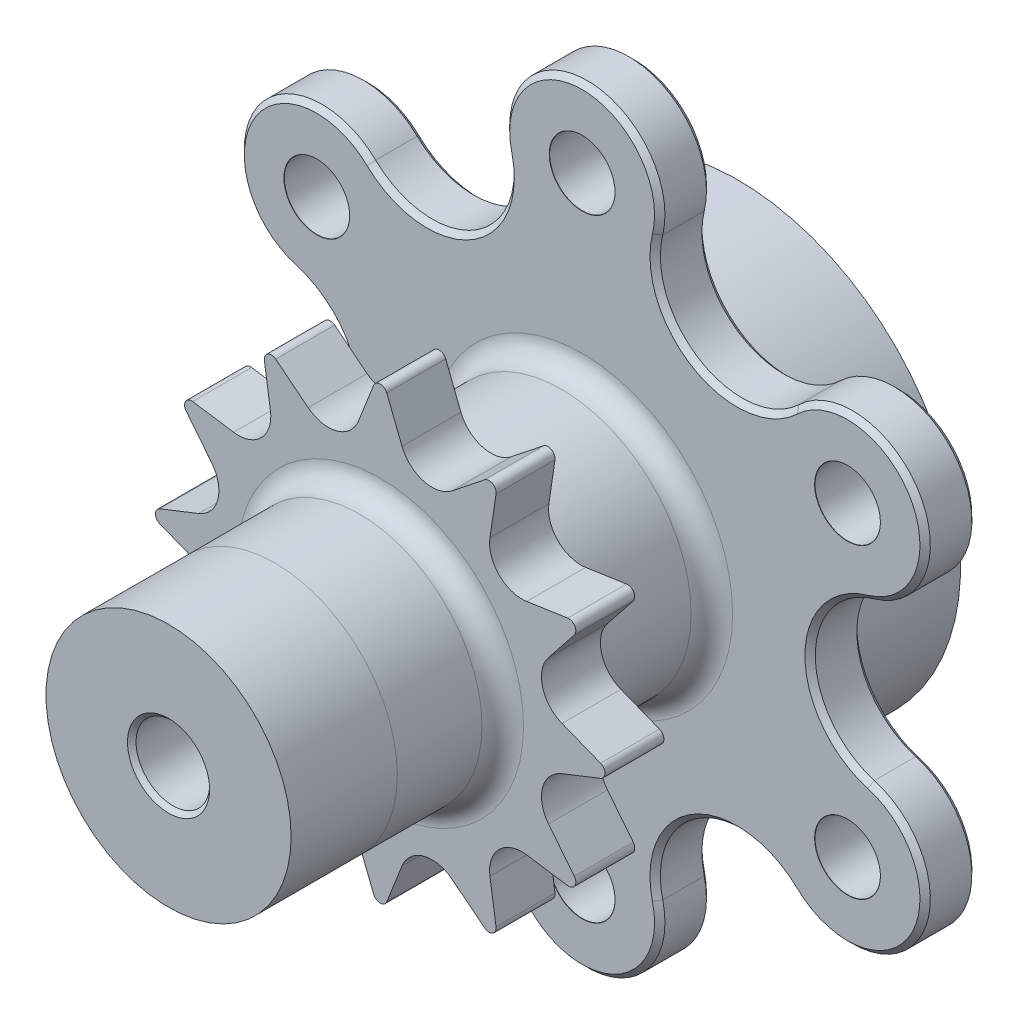
SolidWorks part; units mm, degrees
material "AISI 4130 Steel, normalized at 870C"
ref_plane "Front Plane" through (0, 0, 0) normal (0, 0, 1) x (1, 0, 0)
ref_plane "Top Plane" through (0, 0, 0) normal (0, 1, 0) x (1, 0, 0)
ref_plane "Right Plane" through (0, 0, 0) normal (1, 0, 0) x (0, 0, -1)
sketch "Sketch1" plane through (0, 0, 0) normal (0, 0, 1) x (1, 0, 0)
  circle A0 centre (0, 0) radius 47
  dimension "D1" = 94
extrude "Boss-Extrude1" add sketch "Sketch1" along normal blind 6.35
hole_wizard "Ø8.0mm Dowel Hole1" positions "Sketch3" profile "Sketch4" hole size "Ø8.0" standard "ANSI Metric" end condition through all
sketch "Sketch3" plane through (0, 0, 6.35) normal (0, 0, 1) x (1, 0, 0)
  point P0 (0, -37.5)
  dimension "D1" = 37.5
sketch "Sketch4" plane through (0, -37.5, 6.35) normal (1, 0, 0) x (0, -1, 0)
  line L0 (0, 0) -> (0, 6.35)
  line L1 (0, 6.35) -> (4, 6.35)
  line L2 (4, 6.35) -> (4, 0.025)
  line L3 (4, 0.025) -> (4.025, 0)
  line L5 (4.025, 0) -> (0, 0)
  line L6 (-4, 0.025) -> (-4.025, 0) construction
  line L11 (0, -6.35) -> (0, 107.95) construction
  dimension "Thru Hole Dia." = 8
  dimension "Thru Hole Depth" = 6.35
  dimension "Near C'Sink Dia." = 8.05
  dimension "Near C'Sink Angle" = 90
pattern_circular "CirPattern1" count 6 over 360 about axis through (0, 0, 0) along (0, 0, 1) of "Ø8.0mm Dowel Hole1"
sketch "Sketch5" plane through (0, 0, 6.35) normal (0, 0, 1) x (1, 0, 0)
  circle A0 centre (0, -37.5) radius 9.5 construction
  circle A1 centre (0, 0) radius 47 construction
  circle A2 centre (0, 0) radius 47
  circle A3 centre (-32.476, -18.75) radius 9.5 construction
  circle A4 centre (-32.476, 18.75) radius 9.5 construction
  circle A5 centre (0, 37.5) radius 9.5 construction
  circle A6 centre (32.476, 18.75) radius 9.5 construction
  circle A7 centre (32.476, -18.75) radius 9.5 construction
  circle A8 centre (0, 0) radius 27.9 construction
  arc A9 (-25.9015, 25.6076) -> (-9.2261, 35.2352) centre (-18.963, 32.8449) ccw
  arc A10 (9.2261, 35.2352) -> (25.9015, 25.6076) centre (18.963, 32.8449) ccw
  arc A11 (35.1276, 9.6276) -> (35.1276, -9.6276) centre (37.926, 0) ccw
  arc A12 (25.9015, -25.6076) -> (9.2261, -35.2352) centre (18.963, -32.8449) ccw
  arc A13 (-9.2261, -35.2352) -> (-25.9015, -25.6076) centre (-18.963, -32.8449) ccw
  arc A14 (-35.1276, -9.6276) -> (-35.1276, 9.6276) centre (-37.926, 0) ccw
  arc A15 (-9.2261, 35.2352) -> (9.2261, 35.2352) centre (0, 37.5) cw
  arc A16 (-25.9015, 25.6076) -> (-35.1276, 9.6276) centre (-32.476, 18.75) ccw
  arc A17 (-35.1276, -9.6276) -> (-25.9015, -25.6076) centre (-32.476, -18.75) ccw
  arc A18 (-9.2261, -35.2352) -> (9.2261, -35.2352) centre (0, -37.5) ccw
  arc A19 (25.9015, -25.6076) -> (35.1276, -9.6276) centre (32.476, -18.75) ccw
  arc A20 (25.9015, 25.6076) -> (35.1276, 9.6276) centre (32.476, 18.75) cw
  point P19 (0, 0)
  point P38 (0, 0)
  circle M13 centre (0, 0) radius 47
  dimension "D1" = 6
  dimension "D2" = 55.8
  dimension "D3" = 6
extrude "Cut-Extrude1" cut sketch "Sketch5" against normal through all contours A16 A9 A15 M13 | A10 A20 A2 A15 | A17 A14 A16 A2 | A18 A13 A17 M13 | A19 A12 A18 A2 | A20 A11 A19 M13
chamfer "Chamfer1" distance 0.635 angle 45 24 edges at (-40.7032, 23.5, 6.35) (-27.9, 0, 6.35) (-40.7032, -23.5, 6.35) (-13.95, -24.1621, 6.35) (0, -47, 6.35) (13.95, -24.1621, 6.35) (40.7032, -23.5, 6.35) (27.9, 0, 6.35) (40.7032, 23.5, 6.35) (13.95, 24.1621, 6.35) (0, 47, 6.35) (-13.95, 24.1621, 6.35) (0, -47, 0) (-13.95, -24.1621, 0) (13.95, -24.1621, 0) (-40.7032, -23.5, 0) (40.7032, -23.5, 0) (-27.9, 0, 0) (27.9, 0, 0) (-40.7032, 23.5, 0) (40.7032, 23.5, 0) (-13.95, 24.1621, 0) (13.95, 24.1621, 0) (0, 47, 0)
sketch "Sketch6" [suppressed] plane through (0, 0, 6.35) normal (0, 0, 1) x (1, 0, 0)
  circle A0 centre (0, 0) radius 15.875
  dimension "D1" = 31.75
extrude "Shaft" [suppressed] add sketch "Sketch6" along normal blind 53.848
sketch "Sketch7" [suppressed] plane through (0, 0, 60.198) normal (0, 0, 1) x (1, 0, 0)
  arc A0 (9.097, -5.6181) -> (9.7313, -4.4292) centre (0, 0) ccw
  arc A1 (9.097, -5.6181) -> (9.0986, -5.9863) centre (9.3955, -5.8008) ccw
  arc A2 (10.055, -4.164) -> (9.7313, -4.4292) centre (10.071, -4.5136) ccw
  arc A3 (12.1705, -3.6562) -> (12.3739, -3.4251) centre (12.0362, -3.333) ccw
  arc A4 (12.3739, -3.4251) -> (12.5248, -2.8127) centre (0.0056, -0.0518) ccw
  arc A5 (9.3895, -8.7865) -> (9.8078, -8.3144) centre (0.0056, -0.0518) ccw
  arc A6 (4.2554, -12.1469) -> (4.8452, -11.9232) centre (0.0056, -0.0518) ccw
  arc A7 (-1.8522, -12.7365) -> (-1.2261, -12.8125) centre (0.0056, -0.0518) ccw
  arc A8 (-7.5343, -10.4201) -> (-7.0152, -10.7784) centre (0.0056, -0.0518) ccw
  arc A9 (-11.489, -5.7285) -> (-11.1959, -6.287) centre (0.0056, -0.0518) ccw
  arc A10 (-12.8144, -0.0518) -> (-12.8105, -0.3671) centre (0.0056, -0.0518) ccw
  arc A11 (12.533, -2.7373) -> (12.4521, -2.5135) centre (12.183, -2.7373) ccw
  arc A12 (12.5248, -2.8127) -> (12.533, -2.7373) centre (12.183, -2.7373) ccw
  arc A13 (10.6424, -0.7555) -> (10.815, -1.0808) centre (10.9916, -0.7786) ccw
  arc A14 (10.6424, -0.7555) -> (10.6656, -0.0518) centre (0.0056, -0.0518) ccw
  arc A15 (10.6656, -0.0518) -> (10.6424, 0.6519) centre (0.0056, -0.0518) ccw
  arc A16 (10.815, 0.9772) -> (10.6424, 0.6519) centre (10.9916, 0.6751) ccw
  arc A17 (12.4521, 2.41) -> (12.533, 2.6337) centre (12.183, 2.6337) ccw
  arc A18 (-12.8105, 0.2636) -> (-12.8144, -0.0518) centre (0.0056, -0.0518) ccw
  arc A19 (-11.1959, 6.1834) -> (-11.489, 5.6249) centre (0.0056, -0.0518) ccw
  arc A20 (-7.0152, 10.6748) -> (-7.5343, 10.3165) centre (0.0056, -0.0518) ccw
  arc A21 (-1.2261, 12.7089) -> (-1.8522, 12.6329) centre (0.0056, -0.0518) ccw
  arc A22 (4.8452, 11.8197) -> (4.2554, 12.0433) centre (0.0056, -0.0518) ccw
  arc A23 (9.8078, 8.2108) -> (9.3895, 8.6829) centre (0.0056, -0.0518) ccw
  arc A24 (12.5248, 2.7091) -> (12.3739, 3.3215) centre (0.0056, -0.0518) ccw
  arc A25 (12.533, 2.6337) -> (12.5248, 2.7091) centre (12.183, 2.6337) ccw
  arc A26 (12.3739, 3.3215) -> (12.1705, 3.5526) centre (12.0362, 3.2294) ccw
  arc A27 (9.751, 4.2682) -> (10.055, 4.0604) centre (10.071, 4.4101) ccw
  arc A28 (9.751, 4.2682) -> (9.097, 5.5145) centre (0.0056, -0.0518) ccw
  arc A29 (9.0986, 5.8827) -> (9.097, 5.5145) centre (9.3955, 5.6972) ccw
  arc A30 (9.8901, 7.9852) -> (9.8078, 8.2108) centre (9.5401, 7.9852) ccw
  arc A31 (9.8824, 7.9122) -> (9.8901, 7.9852) centre (9.5401, 7.9852) ccw
  arc A32 (9.3895, 8.6829) -> (9.102, 8.793) centre (9.1333, 8.4444) ccw
  arc A33 (6.6272, 8.3023) -> (5.4688, 9.1018) centre (0.0056, -0.0518) ccw
  arc A34 (6.6272, 8.3023) -> (6.9929, 8.2596) centre (6.8446, 8.5766) ccw
  arc A35 (5.2992, 9.4287) -> (5.4688, 9.1018) centre (5.6482, 9.4024) ccw
  arc A36 (5.0501, 11.5899) -> (4.8452, 11.8197) centre (4.713, 11.4956) ccw
  arc A37 (4.2554, 12.0433) -> (3.9497, 12.0072) centre (4.1394, 11.7131) ccw
  arc A38 (1.9864, 10.4226) -> (0.5891, 10.5922) centre (0.0056, -0.0518) ccw
  arc A39 (1.9864, 10.4226) -> (2.3301, 10.5547) centre (2.0514, 10.7665) ccw
  arc A40 (0.2871, 10.8028) -> (0.5891, 10.5922) centre (0.6083, 10.9417) ccw
  arc A41 (-0.9379, 12.6007) -> (-1.2261, 12.7089) centre (-1.1925, 12.3605) ccw
  arc A42 (-1.8522, 12.6329) -> (-2.1062, 12.4588) centre (-1.8015, 12.2866) ccw
  arc A43 (-3.1082, 10.1433) -> (-4.4242, 9.6442) centre (0.0056, -0.0518) ccw
  arc A44 (-3.1082, 10.1433) -> (-2.8653, 10.42) centre (-3.2104, 10.478) ccw
  arc A45 (-4.7895, 9.6902) -> (-4.4242, 9.6442) centre (-4.5697, 9.9625) ccw
  arc A46 (-6.7097, 10.7129) -> (-7.0152, 10.6748) centre (-6.8235, 10.382) ccw
  arc A47 (-7.5343, 10.3165) -> (-7.6783, 10.0444) centre (-7.3284, 10.0335) ccw
  arc A48 (-7.4894, 7.5284) -> (-7.3855, 7.7773) centre (-7.7355, 7.7773) ccw
  arc A49 (-7.4894, 7.5284) -> (-8.4227, 6.4749) centre (0.0056, -0.0518) ccw
  arc A50 (-7.3855, 7.7773) -> (-7.4029, 7.8863) centre (-7.7355, 7.7773) ccw
  arc A51 (-8.7676, 6.3459) -> (-8.4227, 6.4749) centre (-8.6995, 6.6892) ccw
  arc A52 (-10.9431, 6.3591) -> (-11.1959, 6.1834) centre (-10.8901, 6.0132) ccw
  arc A53 (-11.489, 5.6249) -> (-11.4901, 5.3171) centre (-11.1752, 5.4699) ccw
  arc A54 (-10.1536, 3.177) -> (-10.4904, 1.8105) centre (0.0056, -0.0518) ccw
  arc A55 (-10.1372, 3.2831) -> (-10.2433, 3.5342) centre (-10.4872, 3.2831) ccw
  arc A56 (-10.1536, 3.177) -> (-10.1372, 3.2831) centre (-10.4872, 3.2831) ccw
  arc A57 (-10.7359, 1.536) -> (-10.4904, 1.8105) centre (-10.8351, 1.8716) ccw
  arc A58 (-12.6683, 0.5366) -> (-12.8105, 0.2636) centre (-12.4606, 0.255) ccw
  arc A59 (-12.8105, -0.3671) -> (-12.6683, -0.6402) centre (-12.4606, -0.3585) ccw
  arc A60 (-10.4904, -1.914) -> (-10.7359, -1.6395) centre (-10.8351, -1.9752) ccw
  arc A61 (-10.4904, -1.914) -> (-10.1536, -3.2806) centre (0.0056, -0.0518) ccw
  arc A62 (-10.1372, -3.3866) -> (-10.1536, -3.2806) centre (-10.4872, -3.3866) ccw
  arc A63 (-10.2433, -3.6377) -> (-10.1372, -3.3866) centre (-10.4872, -3.3866) ccw
  arc A64 (-11.4901, -5.4206) -> (-11.489, -5.7285) centre (-11.1752, -5.5735) ccw
  arc A65 (-11.1959, -6.287) -> (-10.9431, -6.4627) centre (-10.8901, -6.1167) ccw
  arc A66 (-8.4227, -6.5785) -> (-8.7676, -6.4495) centre (-8.6995, -6.7928) ccw
  arc A67 (-8.4227, -6.5785) -> (-7.4894, -7.632) centre (0.0056, -0.0518) ccw
  arc A68 (-7.3855, -7.8809) -> (-7.4894, -7.632) centre (-7.7355, -7.8809) ccw
  arc A69 (-7.4029, -7.9899) -> (-7.3855, -7.8809) centre (-7.7355, -7.8809) ccw
  arc A70 (-7.6783, -10.148) -> (-7.5343, -10.4201) centre (-7.3284, -10.137) ccw
  arc A71 (-7.0152, -10.7784) -> (-6.7097, -10.8165) centre (-6.8235, -10.4855) ccw
  arc A72 (-4.4242, -9.7478) -> (-4.7895, -9.7938) centre (-4.5697, -10.0661) ccw
  arc A73 (-4.4242, -9.7478) -> (-3.1082, -10.2469) centre (0.0056, -0.0518) ccw
  arc A74 (-2.8653, -10.5236) -> (-3.1082, -10.2469) centre (-3.2104, -10.5816) ccw
  arc A75 (-2.1062, -12.5624) -> (-1.8522, -12.7365) centre (-1.8015, -12.3901) ccw
  arc A76 (-1.2261, -12.8125) -> (-0.9379, -12.7043) centre (-1.1925, -12.4641) ccw
  arc A77 (0.5891, -10.6958) -> (1.9864, -10.5262) centre (0.0056, -0.0518) ccw
  arc A78 (0.5891, -10.6958) -> (0.2871, -10.9063) centre (0.6083, -11.0453) ccw
  arc A79 (2.3301, -10.6583) -> (1.9864, -10.5262) centre (2.0514, -10.8701) ccw
  arc A80 (3.9497, -12.1108) -> (4.2554, -12.1469) centre (4.1394, -11.8167) ccw
  arc A81 (4.8452, -11.9232) -> (5.0501, -11.6935) centre (4.713, -11.5991) ccw
  arc A82 (5.4688, -9.2054) -> (5.2992, -9.5322) centre (5.6482, -9.506) ccw
  arc A83 (5.4688, -9.2054) -> (6.6272, -8.4059) centre (0.0056, -0.0518) ccw
  arc A84 (6.9929, -8.3632) -> (6.6272, -8.4059) centre (6.8446, -8.6802) ccw
  arc A85 (9.102, -8.8966) -> (9.3895, -8.7865) centre (9.1333, -8.548) ccw
  arc A86 (9.8078, -8.3144) -> (9.8901, -8.0888) centre (9.5401, -8.0888) ccw
  arc A87 (9.8901, -8.0888) -> (9.8824, -8.0157) centre (9.5401, -8.0888) ccw
  circle A88 centre (0, 0) radius 15.875 construction
  circle A89 centre (0, 0) radius 15.875
  spline S0 degree 4 poles (9.0986, -5.9863) (9.1513, -6.0706) (9.2437, -6.2285) (9.367, -6.4648) (9.5091, -6.7844) (9.6282, -7.0962) (9.741, -7.4422) (9.814, -7.7129) (9.8587, -7.9047) (9.8824, -8.0157) knots 0 0 0 0 0 0.181969 0.334561 0.487154 0.639745 0.792337 1 1 1 1 1 weights 1 1 1 1 1 1 1 1 1 1
  spline S1 degree 4 poles (10.055, -4.164) (10.1544, -4.1595) (10.3368, -4.1458) (10.6013, -4.113) (10.9451, -4.0484) (11.2693, -3.9693) (11.6181, -3.8656) (11.8824, -3.7718) (12.0657, -3.6997) (12.1705, -3.6562) knots 0 0 0 0 0 0.181969 0.334561 0.487154 0.639745 0.792337 1 1 1 1 1 weights 1 1 1 1 1 1 1 1 1 1
  spline S2 degree 4 poles (10.815, -1.0808) (10.9008, -1.131) (11.056, -1.2278) (11.275, -1.3798) (11.5494, -1.5968) (11.7997, -1.8175) (12.0603, -2.0714) (12.2508, -2.2773) (12.3796, -2.4263) (12.4521, -2.5135) knots 0 0 0 0 0 0.181969 0.334561 0.487154 0.639745 0.792337 1 1 1 1 1 weights 1 1 1 1 1 1 1 1 1 1
  spline S3 degree 4 poles (10.815, 0.9772) (10.9008, 1.0274) (11.056, 1.1243) (11.275, 1.2762) (11.5494, 1.4932) (11.7997, 1.714) (12.0603, 1.9678) (12.2508, 2.1737) (12.3796, 2.3227) (12.4521, 2.41) knots 0 0 0 0 0 0.181969 0.334561 0.487154 0.639745 0.792337 1 1 1 1 1 weights 1 1 1 1 1 1 1 1 1 1
  spline S4 degree 4 poles (10.055, 4.0604) (10.1544, 4.0559) (10.3368, 4.0422) (10.6013, 4.0095) (10.9451, 3.9448) (11.2693, 3.8657) (11.6181, 3.762) (11.8824, 3.6683) (12.0657, 3.5962) (12.1705, 3.5526) knots 0 0 0 0 0 0.181969 0.334561 0.487154 0.639745 0.792337 1 1 1 1 1 weights 1 1 1 1 1 1 1 1 1 1
  spline S5 degree 4 poles (9.0986, 5.8827) (9.1513, 5.967) (9.2437, 6.1249) (9.367, 6.3612) (9.5091, 6.6809) (9.6282, 6.9927) (9.741, 7.3386) (9.814, 7.6094) (9.8587, 7.8012) (9.8824, 7.9122) knots 0 0 0 0 0 0.181969 0.334561 0.487154 0.639745 0.792337 1 1 1 1 1 weights 1 1 1 1 1 1 1 1 1 1
  spline S6 degree 4 poles (6.9929, 8.2596) (7.083, 8.3017) (7.2508, 8.3744) (7.5002, 8.4683) (7.8347, 8.5709) (8.1586, 8.6515) (8.5156, 8.7218) (8.7932, 8.7616) (8.989, 8.7829) (9.102, 8.793) knots 0 0 0 0 0 0.181969 0.334561 0.487154 0.639745 0.792337 1 1 1 1 1 weights 1 1 1 1 1 1 1 1 1 1
  spline S7 degree 4 poles (5.2992, 9.4287) (5.3067, 9.5278) (5.3151, 9.7106) (5.3144, 9.9771) (5.2917, 10.3262) (5.2522, 10.6576) (5.1914, 11.0163) (5.1302, 11.29) (5.0807, 11.4806) (5.0501, 11.5899) knots 0 0 0 0 0 0.181969 0.334561 0.487154 0.639745 0.792337 1 1 1 1 1 weights 1 1 1 1 1 1 1 1 1 1
  spline S8 degree 4 poles (2.3301, 10.5547) (2.3902, 10.6339) (2.5051, 10.7763) (2.6823, 10.9753) (2.9308, 11.2215) (3.1801, 11.4434) (3.4636, 11.6716) (3.6909, 11.8358) (3.8543, 11.9457) (3.9497, 12.0072) knots 0 0 0 0 0 0.181969 0.334561 0.487154 0.639745 0.792337 1 1 1 1 1 weights 1 1 1 1 1 1 1 1 1 1
  spline S9 degree 4 poles (0.2871, 10.8028) (0.2476, 10.8941) (0.1701, 11.0598) (0.0457, 11.2954) (-0.1366, 11.594) (-0.3256, 11.8691) (-0.5462, 12.1584) (-0.7276, 12.3723) (-0.86, 12.5181) (-0.9379, 12.6007) knots 0 0 0 0 0 0.181969 0.334561 0.487154 0.639745 0.792337 1 1 1 1 1 weights 1 1 1 1 1 1 1 1 1 1
  spline S10 degree 4 poles (-2.8653, 10.42) (-2.8488, 10.5181) (-2.8133, 10.6975) (-2.7488, 10.9561) (-2.6433, 11.2896) (-2.5256, 11.602) (-2.3806, 11.9357) (-2.2557, 12.1868) (-2.162, 12.36) (-2.1062, 12.4588) knots 0 0 0 0 0 0.181969 0.334561 0.487154 0.639745 0.792337 1 1 1 1 1 weights 1 1 1 1 1 1 1 1 1 1
  spline S11 degree 4 poles (-4.7895, 9.6902) (-4.8669, 9.7527) (-5.0125, 9.8635) (-5.2322, 10.0143) (-5.5324, 10.1939) (-5.8276, 10.3497) (-6.1574, 10.5034) (-6.4174, 10.6085) (-6.6024, 10.676) (-6.7097, 10.7129) knots 0 0 0 0 0 0.181969 0.334561 0.487154 0.639745 0.792337 1 1 1 1 1 weights 1 1 1 1 1 1 1 1 1 1
  spline S12 degree 4 poles (-7.4029, 7.8863) (-7.4339, 7.9809) (-7.4858, 8.1563) (-7.549, 8.4152) (-7.6105, 8.7595) (-7.6514, 9.0908) (-7.6782, 9.4537) (-7.6842, 9.734) (-7.6818, 9.931) (-7.6783, 10.0444) knots 0 0 0 0 0 0.181969 0.334561 0.487154 0.639745 0.792337 1 1 1 1 1 weights 1 1 1 1 1 1 1 1 1 1
  spline S13 degree 4 poles (-8.7676, 6.3459) (-8.8652, 6.3653) (-9.0456, 6.3957) (-9.3102, 6.4271) (-9.6595, 6.4467) (-9.9932, 6.4474) (-10.3567, 6.4302) (-10.6357, 6.4025) (-10.8309, 6.3763) (-10.9431, 6.3591) knots 0 0 0 0 0 0.181969 0.334561 0.487154 0.639745 0.792337 1 1 1 1 1 weights 1 1 1 1 1 1 1 1 1 1
  spline S14 degree 4 poles (-10.2433, 3.5342) (-10.3147, 3.6034) (-10.4422, 3.7346) (-10.6184, 3.9345) (-10.8329, 4.2109) (-11.0231, 4.4851) (-11.2154, 4.794) (-11.3511, 5.0395) (-11.4405, 5.215) (-11.4901, 5.3171) knots 0 0 0 0 0 0.181969 0.334561 0.487154 0.639745 0.792337 1 1 1 1 1 weights 1 1 1 1 1 1 1 1 1 1
  spline S15 degree 4 poles (-10.7359, 1.536) (-10.8312, 1.5078) (-11.0051, 1.4509) (-11.254, 1.3558) (-11.5724, 1.2107) (-11.8683, 1.0563) (-12.1821, 0.8722) (-12.4163, 0.7179) (-12.577, 0.604) (-12.6683, 0.5366) knots 0 0 0 0 0 0.181969 0.334561 0.487154 0.639745 0.792337 1 1 1 1 1 weights 1 1 1 1 1 1 1 1 1 1
  spline S16 degree 4 poles (-10.7359, -1.6395) (-10.8312, -1.6113) (-11.0051, -1.5544) (-11.254, -1.4593) (-11.5724, -1.3143) (-11.8683, -1.1599) (-12.1821, -0.9757) (-12.4163, -0.8214) (-12.577, -0.7076) (-12.6683, -0.6402) knots 0 0 0 0 0 0.181969 0.334561 0.487154 0.639745 0.792337 1 1 1 1 1 weights 1 1 1 1 1 1 1 1 1 1
  spline S17 degree 4 poles (-10.2433, -3.6377) (-10.3147, -3.707) (-10.4422, -3.8382) (-10.6184, -4.0381) (-10.8329, -4.3145) (-11.0231, -4.5887) (-11.2154, -4.8976) (-11.3511, -5.143) (-11.4405, -5.3185) (-11.4901, -5.4206) knots 0 0 0 0 0 0.181969 0.334561 0.487154 0.639745 0.792337 1 1 1 1 1 weights 1 1 1 1 1 1 1 1 1 1
  spline S18 degree 4 poles (-8.7676, -6.4495) (-8.8652, -6.4689) (-9.0456, -6.4993) (-9.3102, -6.5307) (-9.6595, -6.5503) (-9.9932, -6.551) (-10.3567, -6.5338) (-10.6357, -6.506) (-10.8309, -6.4799) (-10.9431, -6.4627) knots 0 0 0 0 0 0.181969 0.334561 0.487154 0.639745 0.792337 1 1 1 1 1 weights 1 1 1 1 1 1 1 1 1 1
  spline S19 degree 4 poles (-7.4029, -7.9899) (-7.4339, -8.0844) (-7.4858, -8.2598) (-7.549, -8.5187) (-7.6105, -8.8631) (-7.6514, -9.1944) (-7.6782, -9.5572) (-7.6842, -9.8376) (-7.6818, -10.0345) (-7.6783, -10.148) knots 0 0 0 0 0 0.181969 0.334561 0.487154 0.639745 0.792337 1 1 1 1 1 weights 1 1 1 1 1 1 1 1 1 1
  spline S20 degree 4 poles (-4.7895, -9.7938) (-4.8669, -9.8563) (-5.0125, -9.9671) (-5.2322, -10.1179) (-5.5324, -10.2975) (-5.8276, -10.4533) (-6.1574, -10.607) (-6.4174, -10.712) (-6.6024, -10.7796) (-6.7097, -10.8165) knots 0 0 0 0 0 0.181969 0.334561 0.487154 0.639745 0.792337 1 1 1 1 1 weights 1 1 1 1 1 1 1 1 1 1
  spline S21 degree 4 poles (-2.8653, -10.5236) (-2.8488, -10.6217) (-2.8133, -10.8011) (-2.7488, -11.0597) (-2.6433, -11.3932) (-2.5256, -11.7056) (-2.3806, -12.0393) (-2.2557, -12.2904) (-2.162, -12.4636) (-2.1062, -12.5624) knots 0 0 0 0 0 0.181969 0.334561 0.487154 0.639745 0.792337 1 1 1 1 1 weights 1 1 1 1 1 1 1 1 1 1
  spline S22 degree 4 poles (0.2871, -10.9063) (0.2476, -10.9976) (0.1701, -11.1634) (0.0457, -11.399) (-0.1366, -11.6976) (-0.3256, -11.9727) (-0.5462, -12.262) (-0.7276, -12.4759) (-0.86, -12.6217) (-0.9379, -12.7043) knots 0 0 0 0 0 0.181969 0.334561 0.487154 0.639745 0.792337 1 1 1 1 1 weights 1 1 1 1 1 1 1 1 1 1
  spline S23 degree 4 poles (2.3301, -10.6583) (2.3902, -10.7375) (2.5051, -10.8799) (2.6823, -11.0789) (2.9308, -11.3251) (3.1801, -11.547) (3.4636, -11.7751) (3.6909, -11.9394) (3.8543, -12.0493) (3.9497, -12.1108) knots 0 0 0 0 0 0.181969 0.334561 0.487154 0.639745 0.792337 1 1 1 1 1 weights 1 1 1 1 1 1 1 1 1 1
  spline S24 degree 4 poles (5.2992, -9.5322) (5.3067, -9.6314) (5.3151, -9.8142) (5.3144, -10.0806) (5.2917, -10.4297) (5.2522, -10.7612) (5.1914, -11.1199) (5.1302, -11.3936) (5.0807, -11.5842) (5.0501, -11.6935) knots 0 0 0 0 0 0.181969 0.334561 0.487154 0.639745 0.792337 1 1 1 1 1 weights 1 1 1 1 1 1 1 1 1 1
  spline S25 degree 4 poles (6.9929, -8.3632) (7.083, -8.4053) (7.2508, -8.478) (7.5002, -8.5719) (7.8347, -8.6744) (8.1586, -8.755) (8.5156, -8.8253) (8.7932, -8.8651) (8.989, -8.8865) (9.102, -8.8966) knots 0 0 0 0 0 0.181969 0.334561 0.487154 0.639745 0.792337 1 1 1 1 1 weights 1 1 1 1 1 1 1 1 1 1
extrude "Splines" [suppressed] cut sketch "Sketch7" against normal blind 36.348
sketch "Sketch8" [suppressed] plane through (0, 0, 60.198) normal (0, 0, 1) x (1, 0, 0)
  circle A0 centre (0, 0) radius 9.525
  circle A1 centre (0, 0) radius 14.605
  dimension "D1" = 19.05
  dimension "D2" = 29.21
extrude "Cut-Extrude3" [suppressed] cut sketch "Sketch8" against normal blind 17.272
fillet "Fillet1" [suppressed] radius 3.175
fillet "Fillet2" [suppressed] radius 2.286
chamfer "Chamfer5" [suppressed] distance 0.635 angle 45
chamfer "Chamfer6" [suppressed] distance 0.254 angle 45
hole_wizard "Tap Drill for M10x1.0 Tap3" [suppressed] positions "Sketch18" profile "Sketch19" hole size "M10x1.0" standard "ANSI Metric"
sketch "Sketch18" [suppressed] plane through (0, 0, 60.198) normal (0, 0, 1) x (1, 0, 0)
  point P0 (0, 0)
sketch "Sketch19" [suppressed] plane through (0, 0, 60.198) normal (1, 0, 0) x (0, -1, 0)
  line L0 (0, 0) -> (0, 60.198)
  line L1 (0, 60.198) -> (4.5, 60.198)
  line L2 (4.5, 60.198) -> (4.5, 0.025)
  line L3 (4.5, 0.025) -> (4.525, 0)
  line L5 (4.525, 0) -> (0, 0)
  line L6 (-4.5, 0.025) -> (-4.525, 0) construction
  line L11 (0, -6.35) -> (0, 107.95) construction
  dimension "Thru Hole Dia." = 9
  dimension "Thru Hole Depth" = 60.198
  dimension "Near C'Sink Dia." = 9.05
  dimension "Near C'Sink Angle" = 90
sketch "Sketch9" [suppressed] plane through (0, 0, 6.35) normal (0, 0, 1) x (1, 0, 0)
  circle A0 centre (0, 0) radius 15
  dimension "D1" = 30
extrude "Boss-Extrude2" [suppressed] add sketch "Sketch9" along normal blind 53.34
sketch "Sketch10" [suppressed] plane through (0, 0, 6.35) normal (0, 0, 1) x (1, 0, 0)
  circle A0 centre (0, 0) radius 15.875
  dimension "D1" = 31.75
extrude "Boss-Extrude3" [suppressed] add sketch "Sketch10" along normal blind 37.42
sketch "Sketch11" [suppressed] plane through (0, 0, 59.69) normal (0, 0, 1) x (1, 0, 0)
  arc A0 (9.097, -5.6181) -> (9.7313, -4.4292) centre (0, 0) ccw
  arc A1 (9.097, -5.6181) -> (9.0986, -5.9863) centre (9.3955, -5.8008) ccw
  arc A2 (10.055, -4.164) -> (9.7313, -4.4292) centre (10.071, -4.5136) ccw
  arc A3 (12.1705, -3.6562) -> (12.3739, -3.4251) centre (12.0362, -3.333) ccw
  arc A4 (12.3739, -3.4251) -> (12.5248, -2.8127) centre (0.0056, -0.0518) ccw
  arc A5 (9.3895, -8.7865) -> (9.8078, -8.3144) centre (0.0056, -0.0518) ccw
  arc A6 (4.2554, -12.1469) -> (4.8452, -11.9232) centre (0.0056, -0.0518) ccw
  arc A7 (-1.8522, -12.7365) -> (-1.2261, -12.8125) centre (0.0056, -0.0518) ccw
  arc A8 (-7.5343, -10.4201) -> (-7.0152, -10.7784) centre (0.0056, -0.0518) ccw
  arc A9 (-11.489, -5.7285) -> (-11.1959, -6.287) centre (0.0056, -0.0518) ccw
  arc A10 (-12.8144, -0.0518) -> (-12.8105, -0.3671) centre (0.0056, -0.0518) ccw
  arc A11 (12.533, -2.7373) -> (12.4521, -2.5135) centre (12.183, -2.7373) ccw
  arc A12 (12.5248, -2.8127) -> (12.533, -2.7373) centre (12.183, -2.7373) ccw
  arc A13 (10.6424, -0.7555) -> (10.815, -1.0808) centre (10.9916, -0.7786) ccw
  arc A14 (10.6424, -0.7555) -> (10.6656, -0.0518) centre (0.0056, -0.0518) ccw
  arc A15 (10.6656, -0.0518) -> (10.6424, 0.6519) centre (0.0056, -0.0518) ccw
  arc A16 (10.815, 0.9772) -> (10.6424, 0.6519) centre (10.9916, 0.6751) ccw
  arc A17 (12.4521, 2.41) -> (12.533, 2.6337) centre (12.183, 2.6337) ccw
  arc A18 (-12.8105, 0.2636) -> (-12.8144, -0.0518) centre (0.0056, -0.0518) ccw
  arc A19 (-11.1959, 6.1834) -> (-11.489, 5.6249) centre (0.0056, -0.0518) ccw
  arc A20 (-7.0152, 10.6748) -> (-7.5343, 10.3165) centre (0.0056, -0.0518) ccw
  arc A21 (-1.2261, 12.7089) -> (-1.8522, 12.6329) centre (0.0056, -0.0518) ccw
  arc A22 (4.8452, 11.8197) -> (4.2554, 12.0433) centre (0.0056, -0.0518) ccw
  arc A23 (9.8078, 8.2108) -> (9.3895, 8.6829) centre (0.0056, -0.0518) ccw
  arc A24 (12.5248, 2.7091) -> (12.3739, 3.3215) centre (0.0056, -0.0518) ccw
  arc A25 (12.533, 2.6337) -> (12.5248, 2.7091) centre (12.183, 2.6337) ccw
  arc A26 (12.3739, 3.3215) -> (12.1705, 3.5526) centre (12.0362, 3.2294) ccw
  arc A27 (9.751, 4.2682) -> (10.055, 4.0604) centre (10.071, 4.4101) ccw
  arc A28 (9.751, 4.2682) -> (9.097, 5.5145) centre (0.0056, -0.0518) ccw
  arc A29 (9.0986, 5.8827) -> (9.097, 5.5145) centre (9.3955, 5.6972) ccw
  arc A30 (9.8901, 7.9852) -> (9.8078, 8.2108) centre (9.5401, 7.9852) ccw
  arc A31 (9.8824, 7.9122) -> (9.8901, 7.9852) centre (9.5401, 7.9852) ccw
  arc A32 (9.3895, 8.6829) -> (9.102, 8.793) centre (9.1333, 8.4444) ccw
  arc A33 (6.6272, 8.3023) -> (5.4688, 9.1018) centre (0.0056, -0.0518) ccw
  arc A34 (6.6272, 8.3023) -> (6.9929, 8.2596) centre (6.8446, 8.5766) ccw
  arc A35 (5.2992, 9.4287) -> (5.4688, 9.1018) centre (5.6482, 9.4024) ccw
  arc A36 (5.0501, 11.5899) -> (4.8452, 11.8197) centre (4.713, 11.4956) ccw
  arc A37 (4.2554, 12.0433) -> (3.9497, 12.0072) centre (4.1394, 11.7131) ccw
  arc A38 (1.9864, 10.4226) -> (0.5891, 10.5922) centre (0.0056, -0.0518) ccw
  arc A39 (1.9864, 10.4226) -> (2.3301, 10.5547) centre (2.0514, 10.7665) ccw
  arc A40 (0.2871, 10.8028) -> (0.5891, 10.5922) centre (0.6083, 10.9417) ccw
  arc A41 (-0.9379, 12.6007) -> (-1.2261, 12.7089) centre (-1.1925, 12.3605) ccw
  arc A42 (-1.8522, 12.6329) -> (-2.1062, 12.4588) centre (-1.8015, 12.2866) ccw
  arc A43 (-3.1082, 10.1433) -> (-4.4242, 9.6442) centre (0.0056, -0.0518) ccw
  arc A44 (-3.1082, 10.1433) -> (-2.8653, 10.42) centre (-3.2104, 10.478) ccw
  arc A45 (-4.7895, 9.6902) -> (-4.4242, 9.6442) centre (-4.5697, 9.9625) ccw
  arc A46 (-6.7097, 10.7129) -> (-7.0152, 10.6748) centre (-6.8235, 10.382) ccw
  arc A47 (-7.5343, 10.3165) -> (-7.6783, 10.0444) centre (-7.3284, 10.0335) ccw
  arc A48 (-7.4894, 7.5284) -> (-7.3855, 7.7773) centre (-7.7355, 7.7773) ccw
  arc A49 (-7.4894, 7.5284) -> (-8.4227, 6.4749) centre (0.0056, -0.0518) ccw
  arc A50 (-7.3855, 7.7773) -> (-7.4029, 7.8863) centre (-7.7355, 7.7773) ccw
  arc A51 (-8.7676, 6.3459) -> (-8.4227, 6.4749) centre (-8.6995, 6.6892) ccw
  arc A52 (-10.9431, 6.3591) -> (-11.1959, 6.1834) centre (-10.8901, 6.0132) ccw
  arc A53 (-11.489, 5.6249) -> (-11.4901, 5.3171) centre (-11.1752, 5.4699) ccw
  arc A54 (-10.1536, 3.177) -> (-10.4904, 1.8105) centre (0.0056, -0.0518) ccw
  arc A55 (-10.1372, 3.2831) -> (-10.2433, 3.5342) centre (-10.4872, 3.2831) ccw
  arc A56 (-10.1536, 3.177) -> (-10.1372, 3.2831) centre (-10.4872, 3.2831) ccw
  arc A57 (-10.7359, 1.536) -> (-10.4904, 1.8105) centre (-10.8351, 1.8716) ccw
  arc A58 (-12.6683, 0.5366) -> (-12.8105, 0.2636) centre (-12.4606, 0.255) ccw
  arc A59 (-12.8105, -0.3671) -> (-12.6683, -0.6402) centre (-12.4606, -0.3585) ccw
  arc A60 (-10.4904, -1.914) -> (-10.7359, -1.6395) centre (-10.8351, -1.9752) ccw
  arc A61 (-10.4904, -1.914) -> (-10.1536, -3.2806) centre (0.0056, -0.0518) ccw
  arc A62 (-10.1372, -3.3866) -> (-10.1536, -3.2806) centre (-10.4872, -3.3866) ccw
  arc A63 (-10.2433, -3.6377) -> (-10.1372, -3.3866) centre (-10.4872, -3.3866) ccw
  arc A64 (-11.4901, -5.4206) -> (-11.489, -5.7285) centre (-11.1752, -5.5735) ccw
  arc A65 (-11.1959, -6.287) -> (-10.9431, -6.4627) centre (-10.8901, -6.1167) ccw
  arc A66 (-8.4227, -6.5785) -> (-8.7676, -6.4495) centre (-8.6995, -6.7928) ccw
  arc A67 (-8.4227, -6.5785) -> (-7.4894, -7.632) centre (0.0056, -0.0518) ccw
  arc A68 (-7.3855, -7.8809) -> (-7.4894, -7.632) centre (-7.7355, -7.8809) ccw
  arc A69 (-7.4029, -7.9899) -> (-7.3855, -7.8809) centre (-7.7355, -7.8809) ccw
  arc A70 (-7.6783, -10.148) -> (-7.5343, -10.4201) centre (-7.3284, -10.137) ccw
  arc A71 (-7.0152, -10.7784) -> (-6.7097, -10.8165) centre (-6.8235, -10.4855) ccw
  arc A72 (-4.4242, -9.7478) -> (-4.7895, -9.7938) centre (-4.5697, -10.0661) ccw
  arc A73 (-4.4242, -9.7478) -> (-3.1082, -10.2469) centre (0.0056, -0.0518) ccw
  arc A74 (-2.8653, -10.5236) -> (-3.1082, -10.2469) centre (-3.2104, -10.5816) ccw
  arc A75 (-2.1062, -12.5624) -> (-1.8522, -12.7365) centre (-1.8015, -12.3901) ccw
  arc A76 (-1.2261, -12.8125) -> (-0.9379, -12.7043) centre (-1.1925, -12.4641) ccw
  arc A77 (0.5891, -10.6958) -> (1.9864, -10.5262) centre (0.0056, -0.0518) ccw
  arc A78 (0.5891, -10.6958) -> (0.2871, -10.9063) centre (0.6083, -11.0453) ccw
  arc A79 (2.3301, -10.6583) -> (1.9864, -10.5262) centre (2.0514, -10.8701) ccw
  arc A80 (3.9497, -12.1108) -> (4.2554, -12.1469) centre (4.1394, -11.8167) ccw
  arc A81 (4.8452, -11.9232) -> (5.0501, -11.6935) centre (4.713, -11.5991) ccw
  arc A82 (5.4688, -9.2054) -> (5.2992, -9.5322) centre (5.6482, -9.506) ccw
  arc A83 (5.4688, -9.2054) -> (6.6272, -8.4059) centre (0.0056, -0.0518) ccw
  arc A84 (6.9929, -8.3632) -> (6.6272, -8.4059) centre (6.8446, -8.6802) ccw
  arc A85 (9.102, -8.8966) -> (9.3895, -8.7865) centre (9.1333, -8.548) ccw
  arc A86 (9.8078, -8.3144) -> (9.8901, -8.0888) centre (9.5401, -8.0888) ccw
  arc A87 (9.8901, -8.0888) -> (9.8824, -8.0157) centre (9.5401, -8.0888) ccw
  spline S0 degree 4 poles (9.0986, -5.9863) (9.1513, -6.0706) (9.2437, -6.2285) (9.367, -6.4648) (9.5091, -6.7844) (9.6282, -7.0962) (9.741, -7.4422) (9.814, -7.7129) (9.8587, -7.9047) (9.8824, -8.0157) knots 0 0 0 0 0 0.181969 0.334561 0.487154 0.639745 0.792337 1 1 1 1 1 weights 1 1 1 1 1 1 1 1 1 1
  spline S1 degree 4 poles (10.055, -4.164) (10.1544, -4.1595) (10.3368, -4.1458) (10.6013, -4.113) (10.9451, -4.0484) (11.2693, -3.9693) (11.6181, -3.8656) (11.8824, -3.7718) (12.0657, -3.6997) (12.1705, -3.6562) knots 0 0 0 0 0 0.181969 0.334561 0.487154 0.639745 0.792337 1 1 1 1 1 weights 1 1 1 1 1 1 1 1 1 1
  spline S2 degree 4 poles (10.815, -1.0808) (10.9008, -1.131) (11.056, -1.2278) (11.275, -1.3798) (11.5494, -1.5968) (11.7997, -1.8175) (12.0603, -2.0714) (12.2508, -2.2773) (12.3796, -2.4263) (12.4521, -2.5135) knots 0 0 0 0 0 0.181969 0.334561 0.487154 0.639745 0.792337 1 1 1 1 1 weights 1 1 1 1 1 1 1 1 1 1
  spline S3 degree 4 poles (10.815, 0.9772) (10.9008, 1.0274) (11.056, 1.1243) (11.275, 1.2762) (11.5494, 1.4932) (11.7997, 1.714) (12.0603, 1.9678) (12.2508, 2.1737) (12.3796, 2.3227) (12.4521, 2.41) knots 0 0 0 0 0 0.181969 0.334561 0.487154 0.639745 0.792337 1 1 1 1 1 weights 1 1 1 1 1 1 1 1 1 1
  spline S4 degree 4 poles (10.055, 4.0604) (10.1544, 4.0559) (10.3368, 4.0422) (10.6013, 4.0095) (10.9451, 3.9448) (11.2693, 3.8657) (11.6181, 3.762) (11.8824, 3.6683) (12.0657, 3.5962) (12.1705, 3.5526) knots 0 0 0 0 0 0.181969 0.334561 0.487154 0.639745 0.792337 1 1 1 1 1 weights 1 1 1 1 1 1 1 1 1 1
  spline S5 degree 4 poles (9.0986, 5.8827) (9.1513, 5.967) (9.2437, 6.1249) (9.367, 6.3612) (9.5091, 6.6809) (9.6282, 6.9927) (9.741, 7.3386) (9.814, 7.6094) (9.8587, 7.8012) (9.8824, 7.9122) knots 0 0 0 0 0 0.181969 0.334561 0.487154 0.639745 0.792337 1 1 1 1 1 weights 1 1 1 1 1 1 1 1 1 1
  spline S6 degree 4 poles (6.9929, 8.2596) (7.083, 8.3017) (7.2508, 8.3744) (7.5002, 8.4683) (7.8347, 8.5709) (8.1586, 8.6515) (8.5156, 8.7218) (8.7932, 8.7616) (8.989, 8.7829) (9.102, 8.793) knots 0 0 0 0 0 0.181969 0.334561 0.487154 0.639745 0.792337 1 1 1 1 1 weights 1 1 1 1 1 1 1 1 1 1
  spline S7 degree 4 poles (5.2992, 9.4287) (5.3067, 9.5278) (5.3151, 9.7106) (5.3144, 9.9771) (5.2917, 10.3262) (5.2522, 10.6576) (5.1914, 11.0163) (5.1302, 11.29) (5.0807, 11.4806) (5.0501, 11.5899) knots 0 0 0 0 0 0.181969 0.334561 0.487154 0.639745 0.792337 1 1 1 1 1 weights 1 1 1 1 1 1 1 1 1 1
  spline S8 degree 4 poles (2.3301, 10.5547) (2.3902, 10.6339) (2.5051, 10.7763) (2.6823, 10.9753) (2.9308, 11.2215) (3.1801, 11.4434) (3.4636, 11.6716) (3.6909, 11.8358) (3.8543, 11.9457) (3.9497, 12.0072) knots 0 0 0 0 0 0.181969 0.334561 0.487154 0.639745 0.792337 1 1 1 1 1 weights 1 1 1 1 1 1 1 1 1 1
  spline S9 degree 4 poles (0.2871, 10.8028) (0.2476, 10.8941) (0.1701, 11.0598) (0.0457, 11.2954) (-0.1366, 11.594) (-0.3256, 11.8691) (-0.5462, 12.1584) (-0.7276, 12.3723) (-0.86, 12.5181) (-0.9379, 12.6007) knots 0 0 0 0 0 0.181969 0.334561 0.487154 0.639745 0.792337 1 1 1 1 1 weights 1 1 1 1 1 1 1 1 1 1
  spline S10 degree 4 poles (-2.8653, 10.42) (-2.8488, 10.5181) (-2.8133, 10.6975) (-2.7488, 10.9561) (-2.6433, 11.2896) (-2.5256, 11.602) (-2.3806, 11.9357) (-2.2557, 12.1868) (-2.162, 12.36) (-2.1062, 12.4588) knots 0 0 0 0 0 0.181969 0.334561 0.487154 0.639745 0.792337 1 1 1 1 1 weights 1 1 1 1 1 1 1 1 1 1
  spline S11 degree 4 poles (-4.7895, 9.6902) (-4.8669, 9.7527) (-5.0125, 9.8635) (-5.2322, 10.0143) (-5.5324, 10.1939) (-5.8276, 10.3497) (-6.1574, 10.5034) (-6.4174, 10.6085) (-6.6024, 10.676) (-6.7097, 10.7129) knots 0 0 0 0 0 0.181969 0.334561 0.487154 0.639745 0.792337 1 1 1 1 1 weights 1 1 1 1 1 1 1 1 1 1
  spline S12 degree 4 poles (-7.4029, 7.8863) (-7.4339, 7.9809) (-7.4858, 8.1563) (-7.549, 8.4152) (-7.6105, 8.7595) (-7.6514, 9.0908) (-7.6782, 9.4537) (-7.6842, 9.734) (-7.6818, 9.931) (-7.6783, 10.0444) knots 0 0 0 0 0 0.181969 0.334561 0.487154 0.639745 0.792337 1 1 1 1 1 weights 1 1 1 1 1 1 1 1 1 1
  spline S13 degree 4 poles (-8.7676, 6.3459) (-8.8652, 6.3653) (-9.0456, 6.3957) (-9.3102, 6.4271) (-9.6595, 6.4467) (-9.9932, 6.4474) (-10.3567, 6.4302) (-10.6357, 6.4025) (-10.8309, 6.3763) (-10.9431, 6.3591) knots 0 0 0 0 0 0.181969 0.334561 0.487154 0.639745 0.792337 1 1 1 1 1 weights 1 1 1 1 1 1 1 1 1 1
  spline S14 degree 4 poles (-10.2433, 3.5342) (-10.3147, 3.6034) (-10.4422, 3.7346) (-10.6184, 3.9345) (-10.8329, 4.2109) (-11.0231, 4.4851) (-11.2154, 4.794) (-11.3511, 5.0395) (-11.4405, 5.215) (-11.4901, 5.3171) knots 0 0 0 0 0 0.181969 0.334561 0.487154 0.639745 0.792337 1 1 1 1 1 weights 1 1 1 1 1 1 1 1 1 1
  spline S15 degree 4 poles (-10.7359, 1.536) (-10.8312, 1.5078) (-11.0051, 1.4509) (-11.254, 1.3558) (-11.5724, 1.2107) (-11.8683, 1.0563) (-12.1821, 0.8722) (-12.4163, 0.7179) (-12.577, 0.604) (-12.6683, 0.5366) knots 0 0 0 0 0 0.181969 0.334561 0.487154 0.639745 0.792337 1 1 1 1 1 weights 1 1 1 1 1 1 1 1 1 1
  spline S16 degree 4 poles (-10.7359, -1.6395) (-10.8312, -1.6113) (-11.0051, -1.5544) (-11.254, -1.4593) (-11.5724, -1.3143) (-11.8683, -1.1599) (-12.1821, -0.9757) (-12.4163, -0.8214) (-12.577, -0.7076) (-12.6683, -0.6402) knots 0 0 0 0 0 0.181969 0.334561 0.487154 0.639745 0.792337 1 1 1 1 1 weights 1 1 1 1 1 1 1 1 1 1
  spline S17 degree 4 poles (-10.2433, -3.6377) (-10.3147, -3.707) (-10.4422, -3.8382) (-10.6184, -4.0381) (-10.8329, -4.3145) (-11.0231, -4.5887) (-11.2154, -4.8976) (-11.3511, -5.143) (-11.4405, -5.3185) (-11.4901, -5.4206) knots 0 0 0 0 0 0.181969 0.334561 0.487154 0.639745 0.792337 1 1 1 1 1 weights 1 1 1 1 1 1 1 1 1 1
  spline S18 degree 4 poles (-8.7676, -6.4495) (-8.8652, -6.4689) (-9.0456, -6.4993) (-9.3102, -6.5307) (-9.6595, -6.5503) (-9.9932, -6.551) (-10.3567, -6.5338) (-10.6357, -6.506) (-10.8309, -6.4799) (-10.9431, -6.4627) knots 0 0 0 0 0 0.181969 0.334561 0.487154 0.639745 0.792337 1 1 1 1 1 weights 1 1 1 1 1 1 1 1 1 1
  spline S19 degree 4 poles (-7.4029, -7.9899) (-7.4339, -8.0844) (-7.4858, -8.2598) (-7.549, -8.5187) (-7.6105, -8.8631) (-7.6514, -9.1944) (-7.6782, -9.5572) (-7.6842, -9.8376) (-7.6818, -10.0345) (-7.6783, -10.148) knots 0 0 0 0 0 0.181969 0.334561 0.487154 0.639745 0.792337 1 1 1 1 1 weights 1 1 1 1 1 1 1 1 1 1
  spline S20 degree 4 poles (-4.7895, -9.7938) (-4.8669, -9.8563) (-5.0125, -9.9671) (-5.2322, -10.1179) (-5.5324, -10.2975) (-5.8276, -10.4533) (-6.1574, -10.607) (-6.4174, -10.712) (-6.6024, -10.7796) (-6.7097, -10.8165) knots 0 0 0 0 0 0.181969 0.334561 0.487154 0.639745 0.792337 1 1 1 1 1 weights 1 1 1 1 1 1 1 1 1 1
  spline S21 degree 4 poles (-2.8653, -10.5236) (-2.8488, -10.6217) (-2.8133, -10.8011) (-2.7488, -11.0597) (-2.6433, -11.3932) (-2.5256, -11.7056) (-2.3806, -12.0393) (-2.2557, -12.2904) (-2.162, -12.4636) (-2.1062, -12.5624) knots 0 0 0 0 0 0.181969 0.334561 0.487154 0.639745 0.792337 1 1 1 1 1 weights 1 1 1 1 1 1 1 1 1 1
  spline S22 degree 4 poles (0.2871, -10.9063) (0.2476, -10.9976) (0.1701, -11.1634) (0.0457, -11.399) (-0.1366, -11.6976) (-0.3256, -11.9727) (-0.5462, -12.262) (-0.7276, -12.4759) (-0.86, -12.6217) (-0.9379, -12.7043) knots 0 0 0 0 0 0.181969 0.334561 0.487154 0.639745 0.792337 1 1 1 1 1 weights 1 1 1 1 1 1 1 1 1 1
  spline S23 degree 4 poles (2.3301, -10.6583) (2.3902, -10.7375) (2.5051, -10.8799) (2.6823, -11.0789) (2.9308, -11.3251) (3.1801, -11.547) (3.4636, -11.7751) (3.6909, -11.9394) (3.8543, -12.0493) (3.9497, -12.1108) knots 0 0 0 0 0 0.181969 0.334561 0.487154 0.639745 0.792337 1 1 1 1 1 weights 1 1 1 1 1 1 1 1 1 1
  spline S24 degree 4 poles (5.2992, -9.5322) (5.3067, -9.6314) (5.3151, -9.8142) (5.3144, -10.0806) (5.2917, -10.4297) (5.2522, -10.7612) (5.1914, -11.1199) (5.1302, -11.3936) (5.0807, -11.5842) (5.0501, -11.6935) knots 0 0 0 0 0 0.181969 0.334561 0.487154 0.639745 0.792337 1 1 1 1 1 weights 1 1 1 1 1 1 1 1 1 1
  spline S25 degree 4 poles (6.9929, -8.3632) (7.083, -8.4053) (7.2508, -8.478) (7.5002, -8.5719) (7.8347, -8.6744) (8.1586, -8.755) (8.5156, -8.8253) (8.7932, -8.8651) (8.989, -8.8865) (9.102, -8.8966) knots 0 0 0 0 0 0.181969 0.334561 0.487154 0.639745 0.792337 1 1 1 1 1 weights 1 1 1 1 1 1 1 1 1 1
extrude "Boss-Extrude4" [suppressed] add sketch "Sketch11" along normal blind 19.05
fillet "Fillet3" [suppressed] radius 2.54
chamfer "Chamfer3" [suppressed] distance 0.254 angle 45
chamfer "Chamfer4" [suppressed] distance 0.635 angle 45
hole_wizard "Tap Drill for M10x1.0 Tap2" [suppressed] positions "Sketch16" profile "Sketch17" hole size "M10x1.0" standard "ANSI Metric"
sketch "Sketch16" [suppressed] plane through (0, 0, 78.74) normal (0, 0, 1) x (1, 0, 0)
  point P0 (0, 0)
sketch "Sketch17" [suppressed] plane through (0, 0, 78.74) normal (1, 0, 0) x (0, -1, 0)
  line L0 (0, 0) -> (0, 78.74)
  line L1 (0, 78.74) -> (4.5, 78.74)
  line L2 (4.5, 78.74) -> (4.5, 0.025)
  line L3 (4.5, 0.025) -> (4.525, 0)
  line L5 (4.525, 0) -> (0, 0)
  line L6 (-4.5, 0.025) -> (-4.525, 0) construction
  line L11 (0, -6.35) -> (0, 107.95) construction
  dimension "Thru Hole Dia." = 9
  dimension "Thru Hole Depth" = 78.74
  dimension "Near C'Sink Dia." = 9.05
  dimension "Near C'Sink Angle" = 90
sketch "Sketch20" plane through (0, 0, 0) normal (0, 0, -1) x (-1, 0, 0)
  circle A0 centre (0, 0) radius 27.265
  circle A2 centre (0, 0) radius 23.455
  dimension "D1" = 54.53
  dimension "D2" = 3.81
extrude "Boss-Extrude5" add sketch "Sketch20" along normal blind 12.7
sketch "Sketch21" plane through (0, 0, 6.35) normal (0, 0, 1) x (1, 0, 0)
  circle A0 centre (0, 0) radius 15.875
  dimension "D1" = 31.75
extrude "Boss-Extrude6" add sketch "Sketch21" along normal blind 17.5
sketch "Sketch22" plane through (0, 0, 23.85) normal (0, 0, 1) x (1, 0, 0)
  circle A0 centre (0, 0) radius 27.5082
  dimension "D1" = 55.0164
extrude "Boss-Extrude7" add sketch "Sketch22" along normal blind 7.2136
sketch "Sketch25" plane through (0, 0, 31.0636) normal (0, 0, 1) x (1, 0, 0)
  line L0 (-0.8057, 26.9597) -> (-2.6638, 22.246)
  line L1 (-6.3502, 23.6991) -> (0, 0) construction
  line L2 (-12.7821, 23.7507) -> (-8.8161, 20.5975)
  arc A0 (0, 27.5082) -> (-0.8057, 26.9597) centre (0, 26.6421) ccw
  arc A1 (-13.7541, 23.8228) -> (-12.7821, 23.7507) centre (-13.3211, 23.0728) cw
  arc A2 (-2.6638, 22.246) -> (-8.8161, 20.5975) centre (-6.3502, 23.6991) cw
  arc A3 (0, 27.5082) -> (-13.7541, 23.8228) centre (0, 0) ccw
  circle A4 centre (0, 0) radius 27.5082 construction
  circle A5 centre (0, 0) radius 27.5082 construction
  dimension "D2" = 3.9624
  dimension "D4" = 0.8661
  dimension "D5" = 23.6991
  dimension "D1" = 24.5351
  dimension "D3" = 4.7137
  dimension "D6" = 13.7541
  dimension "D7" = 5.5444
extrude "Cut-Extrude4" cut sketch "Sketch25" against normal blind 7.62
pattern_circular "CirPattern2" count 12 over 360 about axis through (0, 0, 0) along (0, 0, 1) of "Cut-Extrude4"
sketch "Sketch23" plane through (0, 0, 31.0636) normal (0, 0, 1) x (1, 0, 0)
  circle A1 centre (0, 0) radius 15
  dimension "D1" = 30
extrude "Boss-Extrude8" add sketch "Sketch23" along normal blind 25.9
ref_plane "Plane2" through (0, 15, 0) normal (0, 1, 0) x (1, 0, 0)
sketch "Sketch27" plane through (0, 15, 0) normal (0, 1, 0) x (1, 0, 0)
  line L0 (-15, -43.9636) -> (15, -43.9636)
  line L1 (-15, -56.9636) -> (15, -56.9636) construction
  line L2 (-15, -56.9636) -> (15, -56.9636) construction
  dimension "D1" = 13
split line "Split Line3"
hole_wizard "M10x1.0 Tapped Hole1" positions "Sketch28" profile "Sketch29" tap size "M10x1.0" standard "ANSI Metric" end condition through all
sketch "Sketch28" plane through (0, 0, 56.9636) normal (0, 0, 1) x (1, 0, 0)
  point P0 (0, 0)
sketch "Sketch29" plane through (0, 0, 56.9636) normal (1, 0, 0) x (0, -1, 0)
  line L0 (0, 0) -> (0, 69.6636)
  line L1 (0, 69.6636) -> (4.5, 69.6636)
  line L2 (4.5, 69.6636) -> (4.5, 0.525)
  line L3 (4.5, 0.525) -> (5.025, 0)
  line L5 (5.025, 0) -> (0, 0)
  line L6 (-4.5, 0.525) -> (-5.025, 0) construction
  line L11 (0, -6.35) -> (0, 107.95) construction
  dimension "Thru Tap Drill Dia." = 9
  dimension "Thru Tap Drill Depth" = 69.6636
  dimension "Near C'Sink Dia." = 10.05
  dimension "Near C'Sink Angle" = 90
ref_plane "Plane3" through (0, 0, 27.4568) normal (0, 0, 1) x (1, 0, 0)
sketch "Sketch30" plane through (0, 0, 27.4568) normal (0, 0, 1) x (1, 0, 0)
  circle A0 centre (0, 0) radius 24.535 construction
  dimension "D1" = 49.07
fillet "Fillet4" radius 2.54 3 edges at (15.875, 0, 23.85) (15, 0, 31.0636) (15.875, 0, 6.35)
